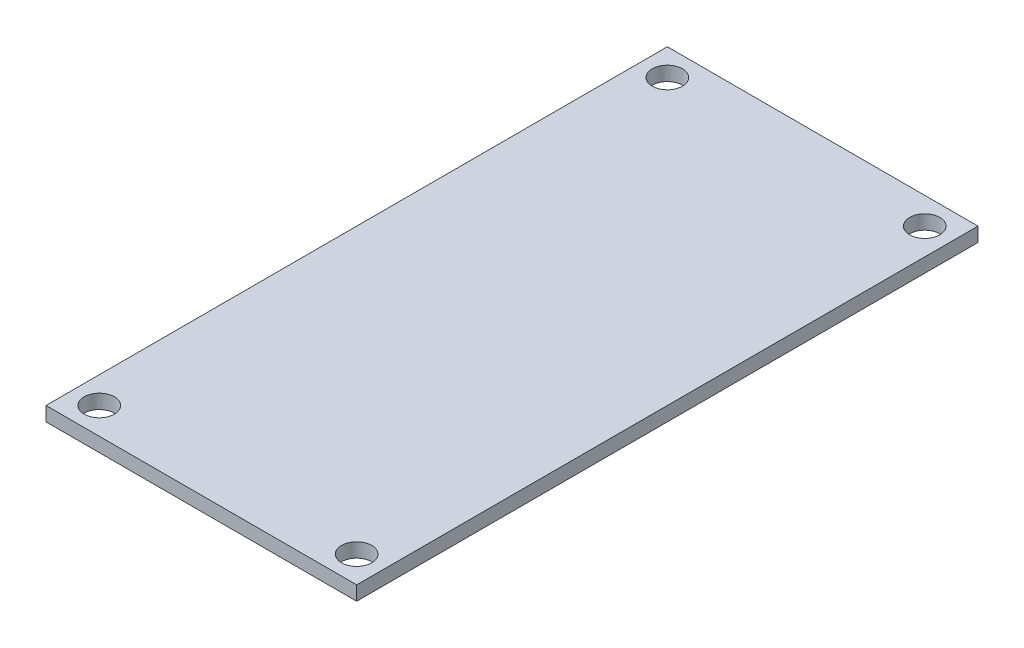
SolidWorks part; units mm, degrees
ref_plane "Front Plane" through (0, 0, 0) normal (0, 0, 1) x (1, 0, 0)
ref_plane "Top Plane" through (0, 0, 0) normal (0, 1, 0) x (1, 0, 0)
ref_plane "Right Plane" through (0, 0, 0) normal (1, 0, 0) x (0, 0, -1)
sketch "Sketch1" plane through (0, 0, 0) normal (0, 1, 0) x (1, 0, 0)
  line L0 (3, 67) -> (0, 67) construction
  line L1 (0, 0) -> (35, 0)
  line L2 (0, 0) -> (0, 70)
  line L3 (0, 70) -> (35, 70)
  line L4 (35, 0) -> (35, 70)
  line L5 (3, 67) -> (32, 67) construction
  line L6 (3, 67) -> (3, 3) construction
  line L7 (3, 3) -> (32, 3) construction
  line L8 (32, 67) -> (32, 3) construction
  line L9 (3, 67) -> (3, 70) construction
  line L10 (32, 3) -> (32, 0) construction
  line L11 (32, 3) -> (35, 3) construction
  circle A0 centre (3, 3) radius 1.7
  circle A1 centre (32, 3) radius 1.7
  circle A2 centre (3, 67) radius 1.7
  circle A3 centre (32, 67) radius 1.7
  dimension "D1" = 3.4
  dimension "D2" = 35
  dimension "D3" = 70
  dimension "D4" = 3
extrude "Boss-Extrude1" add sketch "Sketch1" along normal blind 1.6
